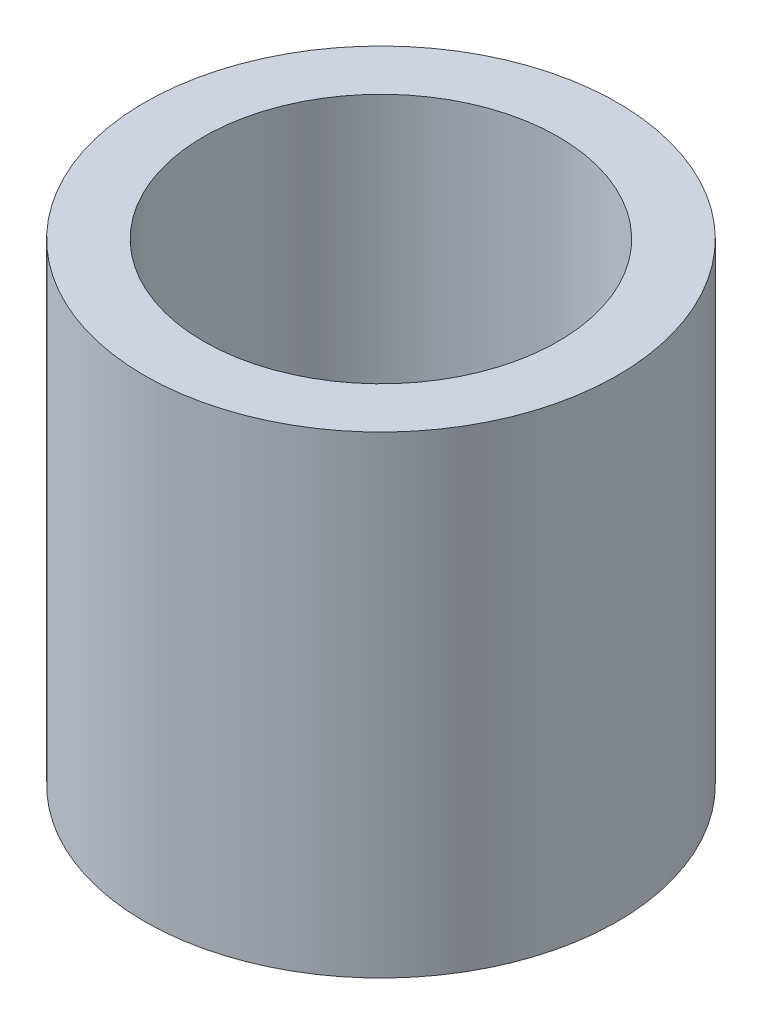
SolidWorks part; units mm, degrees
material "PVC Rigid"
ref_plane "Front Plane" through (0, 0, 0) normal (0, 0, 1) x (1, 0, 0)
ref_plane "Top Plane" through (0, 0, 0) normal (0, 1, 0) x (1, 0, 0)
ref_plane "Right Plane" through (0, 0, 0) normal (1, 0, 0) x (0, 0, -1)
sketch "Sketch1" plane through (0, 0, 0) normal (0, 1, 0) x (1, 0, 0)
  circle A0 centre (0, 0) radius 12.7
  dimension "D1" = 25.4
extrude "Boss-Extrude1" add sketch "Sketch1" along normal blind 25.4
sketch "Sketch2" plane through (0, 25.4, 0) normal (0, 1, 0) x (1, 0, 0)
  circle A0 centre (0, 0) radius 9.525
  dimension "D1" = 19.05
extrude "Cut-Extrude1" cut sketch "Sketch2" against normal blind 22.225
sketch "Sketch3" plane through (0, 3.175, 0) normal (0, 1, 0) x (1, 0, 0)
  circle A0 centre (0, 0) radius 2.54
  dimension "D1" = 5.08
extrude "Cut-Extrude2" cut sketch "Sketch3" against normal through all
